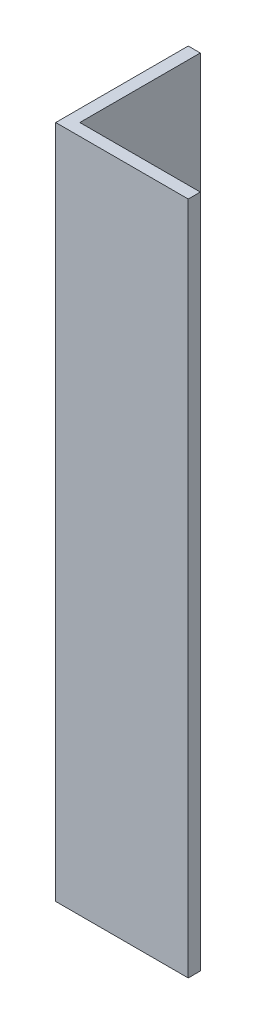
SolidWorks part; units mm, degrees
ref_plane "Спереди" through (0, 0, 0) normal (0, 0, 1) x (1, 0, 0)
ref_plane "Сверху" through (0, 0, 0) normal (0, 1, 0) x (1, 0, 0)
ref_plane "Справа" through (0, 0, 0) normal (1, 0, 0) x (0, 0, -1)
sketch "Эскиз1" plane through (0, 0, 0) normal (0, 1, 0) x (1, 0, 0)
  line L0 (0, -1.0719) -> (0, -21.0719)
  line L1 (0, -21.0719) -> (20, -21.0719)
  line L2 (20, -21.0719) -> (20, -23.0719)
  line L3 (20, -23.0719) -> (-2, -23.0719)
  line L4 (-2, -23.0719) -> (-2, -1.0719)
  line L5 (-2, -1.0719) -> (0, -1.0719)
extrude "Вытянуть1" add sketch "Эскиз1" along normal blind 112
